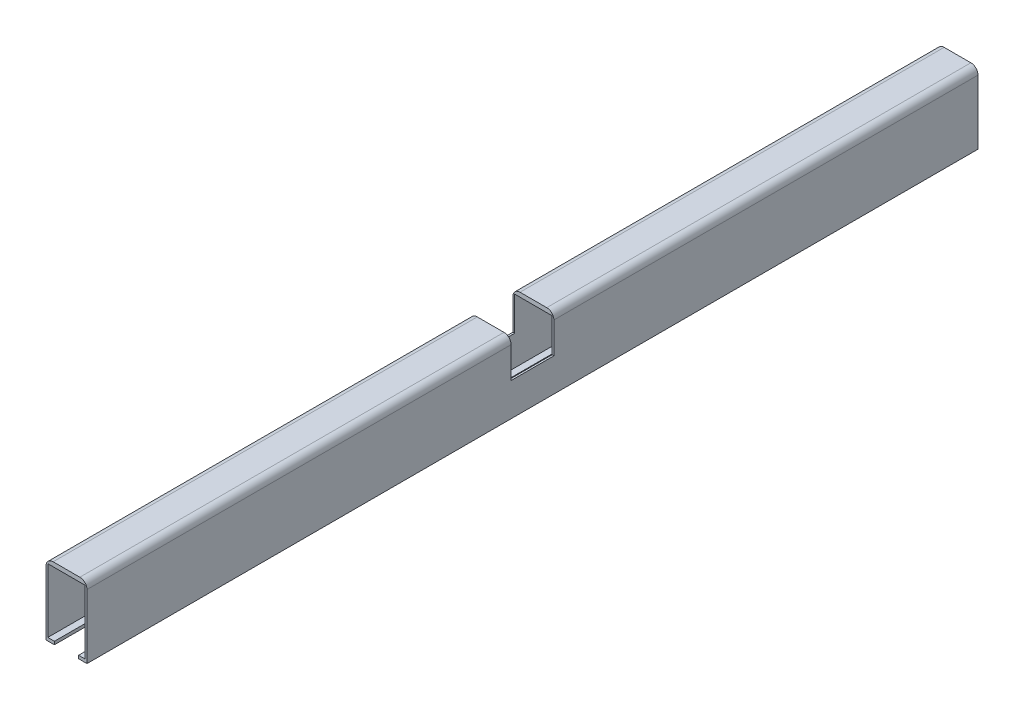
SolidWorks part; units mm, degrees
ref_plane "Front Plane" through (0, 0, 0) normal (0, 0, 1) x (1, 0, 0)
ref_plane "Top Plane" through (0, 0, 0) normal (0, 1, 0) x (1, 0, 0)
ref_plane "Right Plane" through (0, 0, 0) normal (1, 0, 0) x (0, 0, -1)
sketch "Sketch1" plane through (0, 0, 0) normal (0, 0, 1) x (1, 0, 0)
  line L0 (0, 0) -> (0, 40) construction
  line L1 (6.785, 0) -> (6.785, 1.73)
  line L2 (6.785, 0) -> (11.5, 0)
  line L3 (11.5, 0) -> (11.5, 36)
  line L4 (6.785, 1.73) -> (10.485, 1.73)
  line L5 (10.485, 1.73) -> (10.485, 37.58)
  line L6 (7.5, 40) -> (-7.5, 40)
  line L7 (10.485, 37.58) -> (-10.485, 37.58)
  line L8 (-10.485, 1.73) -> (-10.485, 37.58)
  line L9 (-6.785, 1.73) -> (-10.485, 1.73)
  line L10 (-11.5, 0) -> (-11.5, 36)
  line L11 (-6.785, 0) -> (-11.5, 0)
  line L12 (-6.785, 0) -> (-6.785, 1.73)
  arc A0 (11.5, 36) -> (7.5, 40) centre (7.5, 36) ccw
  arc A1 (-11.5, 36) -> (-7.5, 40) centre (-7.5, 36) cw
  point P16 (0, 37.58)
  dimension "D7" = 4
  dimension "D1" = 40
  dimension "D2" = 13.57
  dimension "D3" = 23
  dimension "D4" = 1.73
  dimension "D5" = 20.97
  dimension "D6" = 2.42
extrude "Boss-Extrude1" add sketch "Sketch1" along normal mid plane 500
sketch "Sketch2" plane through (0, 0, 0) normal (1, 0, 0) x (0, 0, -1)
  line L1 (-250, 40) -> (250, 40) construction
  line L2 (-12, 40) -> (12, 40)
  line L3 (-12, 40) -> (-12, 18.58)
  line L4 (-12, 18.58) -> (12, 18.58)
  line L5 (12, 40) -> (12, 18.58)
  point P6 (0, 18.58)
  dimension "D1" = 24
  dimension "D2" = 21.42
extrude "Cut-Extrude1" cut sketch "Sketch2" against normal up to next and the other way up to next
